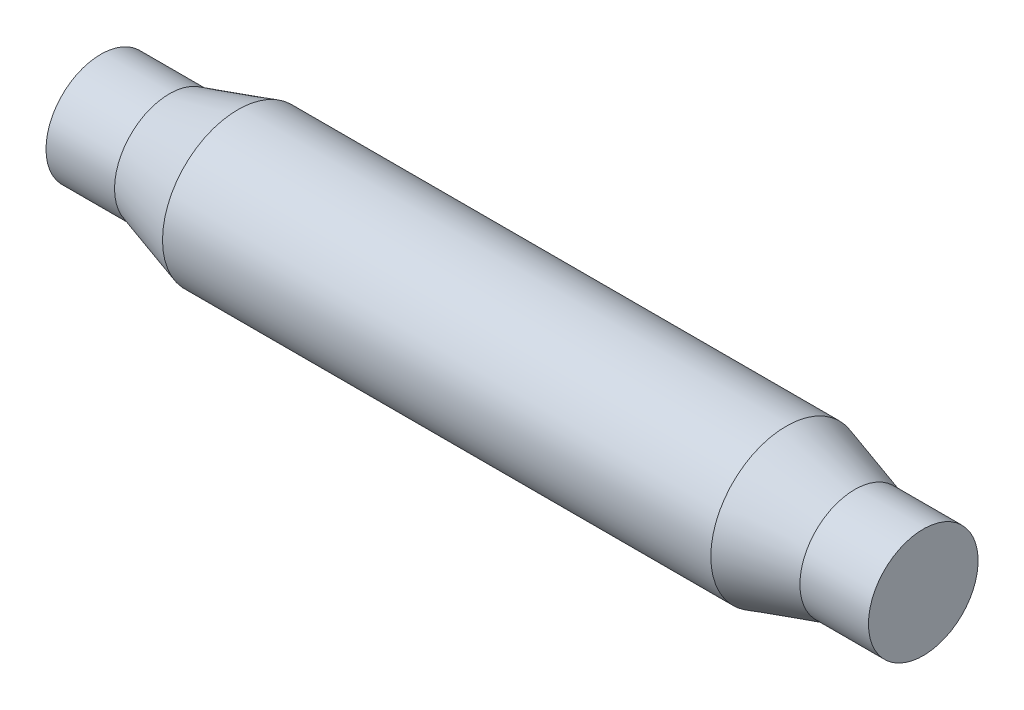
SolidWorks part; units mm, degrees
ref_plane "Plan de face" through (0, 0, 0) normal (0, 0, 1) x (1, 0, 0)
ref_plane "Plan de dessus" through (0, 0, 0) normal (0, 1, 0) x (1, 0, 0)
ref_plane "Plan de droite" through (0, 0, 0) normal (1, 0, 0) x (0, 0, -1)
sketch "Esquisse2" plane through (0, 0, 0) normal (0, 1, 0) x (1, 0, 0)
  line L0 (-30, 0) -> (30, 0)
  line L1 (30, 0) -> (30, 4)
  line L2 (30, 4) -> (25, 4)
  line L3 (25, 4) -> (20, 5.5)
  line L4 (20, 5.5) -> (-20, 5.5)
  line L6 (-30, 4) -> (-25, 4)
  line L7 (-30, 0) -> (-30, 4)
  line L8 (-25, 4) -> (-20, 5.5)
  dimension "D1" = 4
  dimension "D3" = 5
revolve "Révolution2" add sketch "Esquisse2" angle 360 about L0
